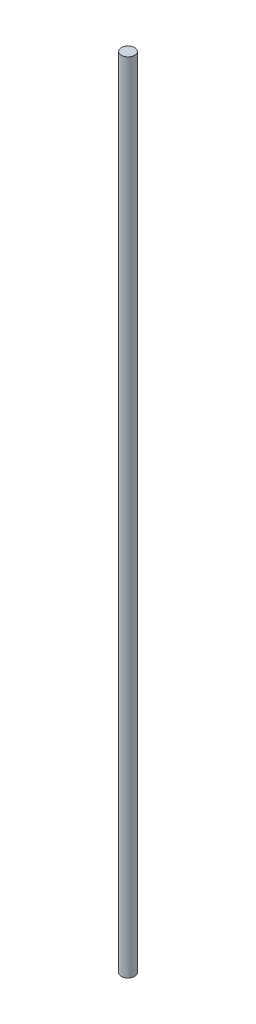
SolidWorks part; units mm, degrees
material "Plain Carbon Steel"
ref_plane "Front Plane" through (0, 0, 0) normal (0, 0, 1) x (1, 0, 0)
ref_plane "Top Plane" through (0, 0, 0) normal (0, 1, 0) x (1, 0, 0)
ref_plane "Right Plane" through (0, 0, 0) normal (1, 0, 0) x (0, 0, -1)
sketch "Sketch1" plane through (0, 0, 0) normal (0, 1, 0) x (1, 0, 0)
  circle A0 centre (0, 0) radius 3.175
  dimension "D1" = 6.35
extrude "Boss-Extrude1" add sketch "Sketch1" along normal blind 381 contours A0
